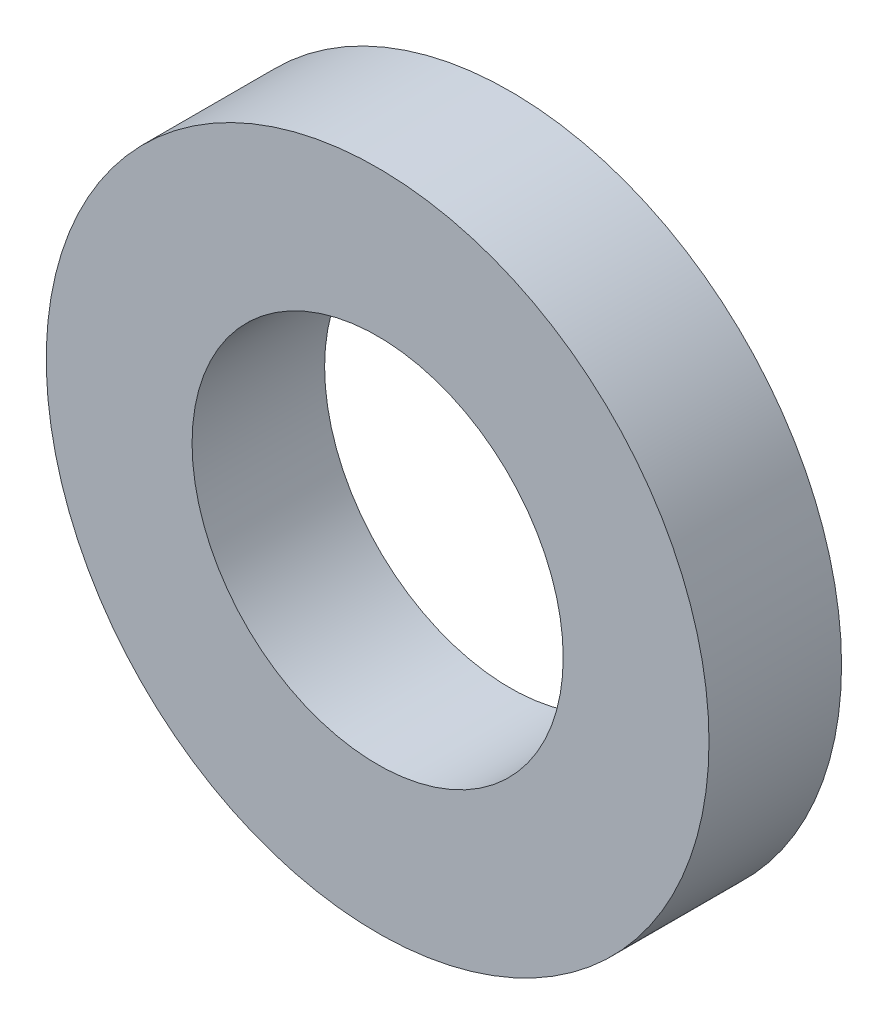
SolidWorks part; units mm, degrees
ref_plane "前视基准面" through (0, 0, 0) normal (0, 0, 1) x (1, 0, 0)
ref_plane "上视基准面" through (0, 0, 0) normal (0, 1, 0) x (1, 0, 0)
ref_plane "右视基准面" through (0, 0, 0) normal (1, 0, 0) x (0, 0, -1)
other "Configuration Table"
sketch "草图1" plane through (0, 0, 0) normal (0, 0, 1) x (1, 0, 0)
  circle A0 centre (0, 0) radius 2.5
  circle A1 centre (0, 0) radius 1.4
extrude "One_mm_alignment_shim" add sketch "草图1" along normal blind 1 from offset 9
